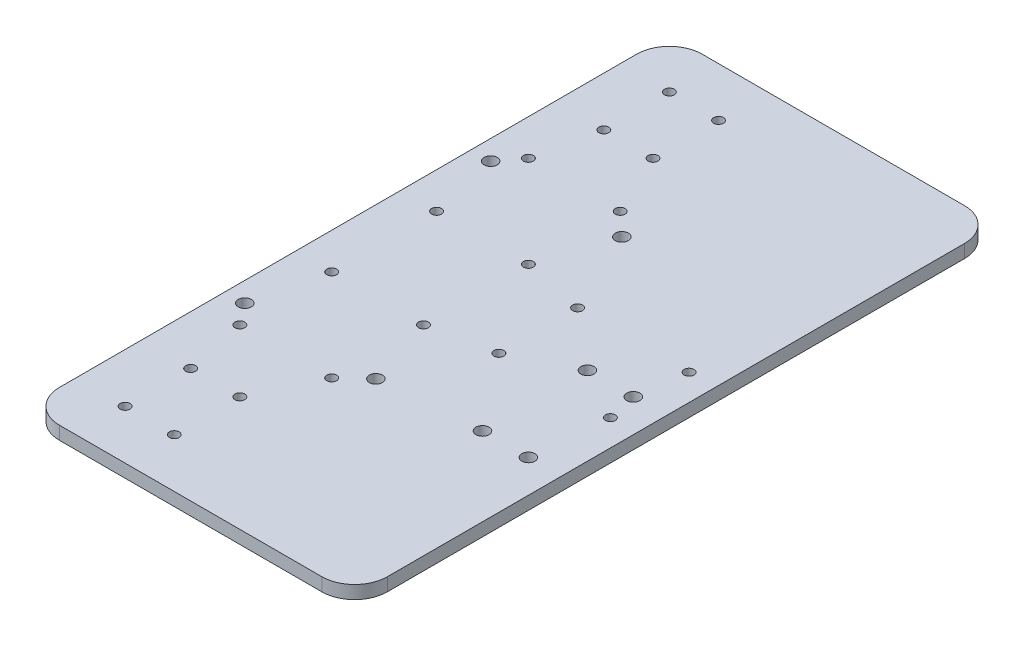
SolidWorks part; units mm, degrees
ref_plane "前视基准面" through (0, 0, 0) normal (0, 0, 1) x (1, 0, 0)
ref_plane "上视基准面" through (0, 0, 0) normal (0, 1, 0) x (1, 0, 0)
ref_plane "右视基准面" through (0, 0, 0) normal (1, 0, 0) x (0, 0, -1)
other "Configuration Table"
sketch "草图1" plane through (0, 0, 0) normal (0, 1, 0) x (1, 0, 0)
  line L0 (-50, -80) -> (50, -80)
  line L1 (-50, -80) -> (-50, 80)
  line L2 (-50, 80) -> (50, 80)
  line L3 (50, -80) -> (50, 80)
  line L4 (-50, -80) -> (50, 80) construction
  line L5 (-50, 80) -> (50, -80) construction
  point P0 (0, 0)
  dimension "D1" = 160
  dimension "D2" = 100
extrude "凸台-拉伸1" add sketch "草图1" along normal blind 4
sketch "草图2" plane through (0, 4, 0) normal (0, 1, 0) x (1, 0, 0)
  line L0 (-50, -80) -> (50, -80) construction
  line L1 (50, -80) -> (50, 80) construction
  circle A0 centre (40, -3) radius 2
  circle A1 centre (26, -3) radius 2
  circle A2 centre (40, -35) radius 2
  circle A3 centre (26, -35) radius 2
  dimension "D1" = 4
  dimension "D2" = 4
  dimension "D3" = 14
  dimension "D4" = 32
  dimension "D5" = 45
  dimension "D6" = 10
extrude "切除-拉伸1" cut sketch "草图2" against normal blind 4
sketch "草图3" plane through (0, 4, 0) normal (0, 1, 0) x (1, 0, 0)
  line L1 (-39, 44) -> (-11, 44) construction
  line L2 (-39, 44) -> (-39, 16) construction
  line L3 (-39, 16) -> (-11, 16) construction
  line L4 (-11, 44) -> (-11, 16) construction
  line L5 (-39, 44) -> (-11, 16) construction
  line L6 (-39, 16) -> (-11, 44) construction
  circle A0 centre (-39, 44) radius 1.5
  circle A1 centre (-11, 44) radius 1.5
  circle A2 centre (-11, 16) radius 1.5
  circle A3 centre (-39, 16) radius 1.5
  point P0 (-25, 30)
  dimension "D3" = 3
  dimension "D1" = 28
  dimension "D2" = 25
  dimension "D4" = 16
extrude "切除-拉伸2" cut sketch "草图3" against normal blind 4
mirror "镜向1" about plane through (0, 0, 0) normal (0, 0, 1) of "切除-拉伸2"
sketch "草图4" plane through (0, 4, 0) normal (0, 1, 0) x (1, 0, 0)
  line L0 (25, 80) -> (25, -80) construction
  line L1 (-50, 0) -> (50, 0) construction
  line L2 (-50, 80) -> (-50, -80) construction
  line L3 (50, -80) -> (50, 80) construction
  line L4 (50, 80) -> (-50, 80) construction
  line L5 (-50, -80) -> (50, -80) construction
  circle A0 centre (42, 12) radius 1.5
  circle A1 centre (8, 12) radius 1.5
  circle A2 centre (42, -12) radius 1.5
  circle A3 centre (8, -12) radius 1.5
  dimension "D1" = 3
  dimension "D2" = 24
  dimension "D3" = 34
  dimension "D4" = 25
extrude "切除-拉伸3" cut sketch "草图4" against normal blind 4
sketch "草图6" plane through (0, 0, -80) normal (0, 0, -1) x (-1, 0, 0)
  line L4 (-50, 0) -> (50, 0)
  line L5 (50, 0) -> (50, 4)
  line L6 (50, 4) -> (-50, 4)
  line L7 (-50, 4) -> (-50, 0)
  line L8 (-50, 0) -> (50, 0)
  line L9 (50, 0) -> (50, 4)
  line L10 (50, 4) -> (-50, 4)
  line L11 (-50, 4) -> (-50, 0)
  dimension "D1" = 0
extrude "凸台-拉伸2" add sketch "草图6" along normal blind 18
sketch "草图5" plane through (0, 4, 0) normal (0, 1, 0) x (1, 0, 0)
  line L0 (0, 0) -> (50000, 0) construction
  line L1 (-50, 98) -> (-50, -80) construction
  circle A0 centre (-35, 83) radius 1.5
  dimension "D1" = 3
  dimension "D2" = 83
  dimension "D3" = 15
extrude "切除-拉伸4" cut sketch "草图5" against normal blind 10
mirror "镜向2" about plane through (0, 0, 0) normal (0, 0, 1) of "凸台-拉伸2"
pattern_linear "阵列(线性)1" count 2 spacing 20 along (0, 0, 1) count 2 spacing 15 along (1, 0, 0) of "切除-拉伸4"
mirror "镜向3" about plane through (0, 0, 0) normal (0, 0, 1) of "阵列(线性)1", "切除-拉伸4"
fillet "圆角1" radius 10 4 edges at (50, 2, 98) (-50, 2, 98) (50, 2, -98) (-50, 2, -98)
sketch "草图7" plane through (0, 4, 0) normal (0, 1, 0) x (1, 0, 0)
  line L0 (-50, 88) -> (-50, -88) construction
  line L1 (-4, -37.5) -> (-44, -37.5) construction
  line L2 (-4, -37.5) -> (-4, 37.5) construction
  line L3 (-4, 37.5) -> (-44, 37.5) construction
  line L4 (-44, -37.5) -> (-44, 37.5) construction
  line L5 (-4, -37.5) -> (-44, 37.5) construction
  line L6 (-4, 37.5) -> (-44, -37.5) construction
  circle A0 centre (-44, 37.5) radius 2
  circle A1 centre (-4, 37.5) radius 2
  circle A2 centre (-4, -37.5) radius 2
  circle A3 centre (-44, -37.5) radius 2
  point P0 (-24, 0)
  dimension "D4" = 4
  dimension "D1" = 75
  dimension "D2" = 40
  dimension "D3" = 6
extrude "切除-拉伸5" cut sketch "草图7" against normal blind 10
